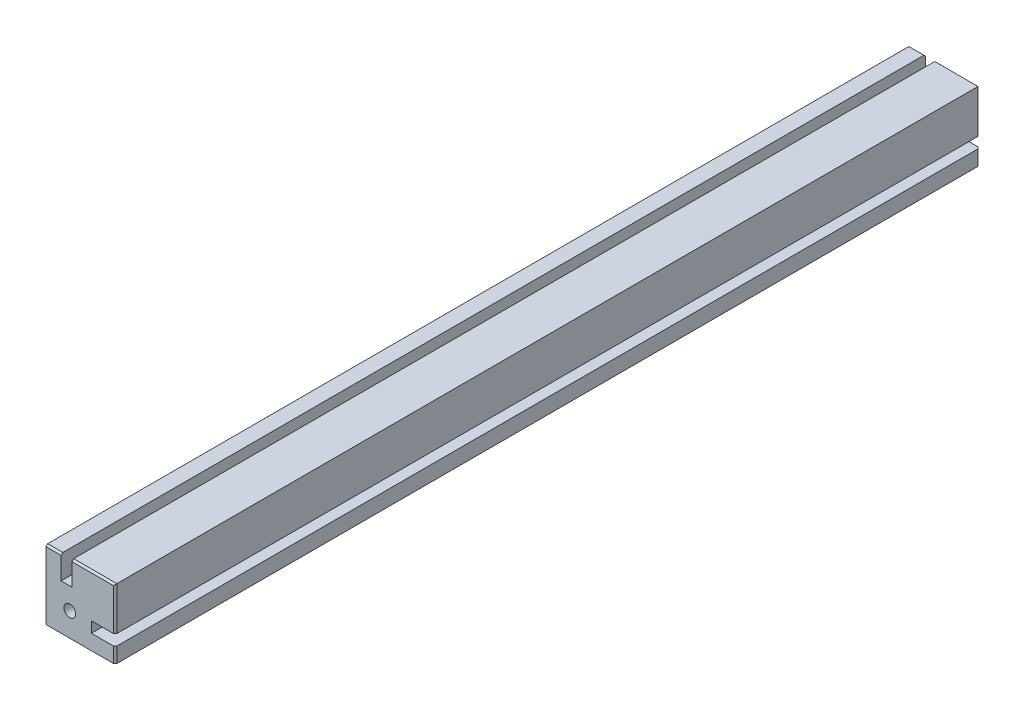
SolidWorks part; units mm, degrees
ref_plane "Plan de face" through (0, 0, 0) normal (0, 0, 1) x (1, 0, 0)
ref_plane "Plan de dessus" through (0, 0, 0) normal (0, 1, 0) x (1, 0, 0)
ref_plane "Plan de droite" through (0, 0, 0) normal (1, 0, 0) x (0, 0, -1)
sketch "Esquisse1" plane through (0, 0, 0) normal (0, 0, 1) x (1, 0, 0)
  line L1 (-8, 8) -> (8, 8)
  line L2 (-8, 8) -> (-8, -8)
  line L3 (-8, -8) -> (8, -8)
  line L4 (8, 8) -> (8, -8)
  line L5 (-8, 8) -> (8, -8) construction
  line L6 (-8, -8) -> (8, 8) construction
  point P0 (0, 0)
  dimension "D1" = 16
extrude "Boss.-Extru.1" add sketch "Esquisse1" along normal blind 200
sketch "Esquisse2" plane through (0, 0, 200) normal (0, 0, 1) x (1, 0, 0)
  line L0 (8, 8) -> (-8, 8) construction
  line L1 (-4.5, 8) -> (-2, 8)
  line L2 (-4.5, 8) -> (-4.5, 2.5)
  line L3 (-4.5, 2.5) -> (-2, 2.5)
  line L4 (-2, 8) -> (-2, 2.5)
  line L5 (8, -8) -> (8, 8) construction
  line L6 (8, -4.5) -> (2.5, -4.5)
  line L7 (8, -4.5) -> (8, -2)
  line L8 (8, -2) -> (2.5, -2)
  line L9 (2.5, -4.5) -> (2.5, -2)
  dimension "D1" = 5.5
  dimension "D2" = 2.5
  dimension "D3" = 10
  dimension "D4" = 10
extrude "Enlèv. mat.-Extru.1" cut sketch "Esquisse2" against normal through all
chamfer "Chanfrein1" distance 0.4 angle 45 8 edges at (8, -6.25, 200) (8, 3, 200) (3, 8, 200) (-6.25, 8, 200) (8, -6.25, 0) (8, 3, 0) (-6.25, 8, 0) (3, 8, 0)
hole_wizard "Dégagement M2.51" positions "Esquisse3D1" profile "Esquisse8" hole size "M2.5" standard "ISO"
sketch3d "Esquisse3D1"
  line L0 (-8, 7.6, 0) -> (-8, -8, 0) construction
  line L1 (-8, -8, 0) -> (7.6, -8, 0) construction
  line L2 (-8, 7.6, 200) -> (-8, -8, 200) construction
  line L3 (-8, -8, 200) -> (7.6, -8, 200) construction
  point P0 (-2.5, -2.5, 200)
  point P2 (-2.5, -2.5, 0)
  dimension "D1" = 5.5
  dimension "D2" = 5.5
  dimension "D3" = 5.5
  dimension "D4" = 5.5
sketch "Esquisse8" plane through (-2.5, -2.5, 200) normal (1, 0, 0) x (0, -1, 0)
  line L0 (0, 0) -> (0, 15)
  line L1 (0, 15) -> (1.35, 14.1888)
  line L2 (1.35, 14.1888) -> (1.35, 0)
  line L5 (1.35, 0) -> (0, 0)
  line L10 (0, 15) -> (-1.35, 14.1888) construction
  line L11 (0, -6.35) -> (0, 107.95) construction
  dimension "Diamètre du perçage" = 2.7
  dimension "Profondeur du perçage" = 15
  dimension "Angle de pointe" = 118
